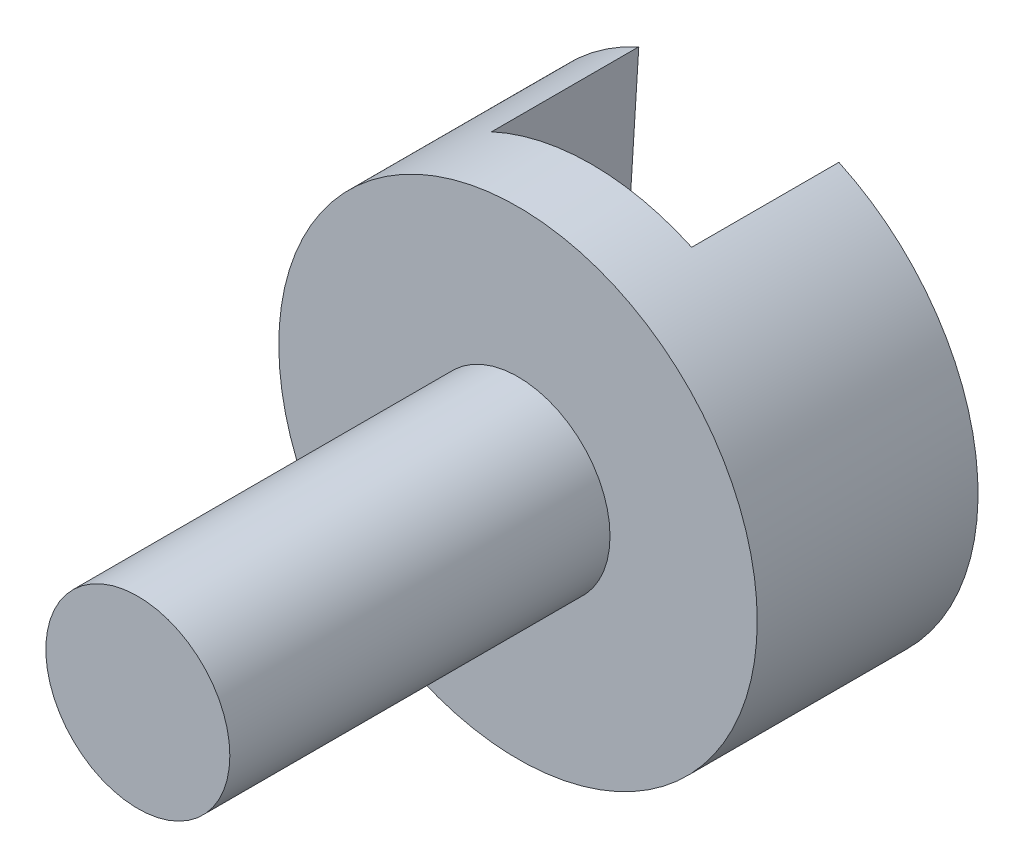
SolidWorks part; units mm, degrees
ref_plane "Front Plane" through (0, 0, 0) normal (0, 0, 1) x (1, 0, 0)
ref_plane "Top Plane" through (0, 0, 0) normal (0, 1, 0) x (1, 0, 0)
ref_plane "Right Plane" through (0, 0, 0) normal (1, 0, 0) x (0, 0, -1)
sketch "Sketch4" plane through (0, 0, 0) normal (0, 0, 1) x (1, 0, 0)
  circle A0 centre (0, 0) radius 3.5 construction
  circle A1 centre (0, 0) radius 6.5
  dimension "D1" = 7
  dimension "D2" = 3
extrude "Boss-Extrude1" add sketch "Sketch4" along normal blind 6 contours A1
sketch "Sketch5" plane through (0, 0, 0) normal (0, 0, 1) x (1, 0, 0)
  line L0 (-2.75, 2.1651) -> (-2.5124, 5.9948)
  line L2 (0, -2.2) -> (0, 2.2) construction
  line L3 (2.75, 2.1651) -> (2.5124, 5.9948)
  circle A0 centre (0, 0) radius 3.5
  circle A1 centre (0, 0) radius 6.5 construction
  circle A2 centre (0, 0) radius 6.5
  dimension "D1" = 7
  dimension "D2" = 5.5
  dimension "D3" = 7.1
sketch "Sketch6" plane through (0, 0, 0) normal (0, 0, 1) x (1, 0, 0)
  line L8 (2.9496, 2.1774) -> (2.712, 6.0072)
  line L9 (2.9458, 2.2388) -> (2.7184, 5.9043)
  line L11 (-2.9496, 2.1774) -> (-2.712, 6.0072)
  line L12 (-2.9458, 2.2388) -> (-2.7184, 5.9043)
  circle A5 centre (0, 0) radius 6.5 construction
  circle A6 centre (0, 0) radius 3.7
  arc A7 (-2.9458, 2.2388) -> (2.9458, 2.2388) centre (0, 0) ccw
  arc A8 (2.7184, 5.9043) -> (-2.7184, 5.9043) centre (0, 0) ccw
  dimension "D1" = 0.2
  dimension "D2" = 0.2
  dimension "D3" = 0.2
extrude "Cut-Extrude2" cut sketch "Sketch6" along normal blind 4
sketch "Sketch7" plane through (0, 0, 6) normal (0, 0, 1) x (1, 0, 0)
  circle A0 centre (0, 0) radius 2.5
  dimension "D1" = 5
extrude "Boss-Extrude2" add sketch "Sketch7" along normal blind 10.33
